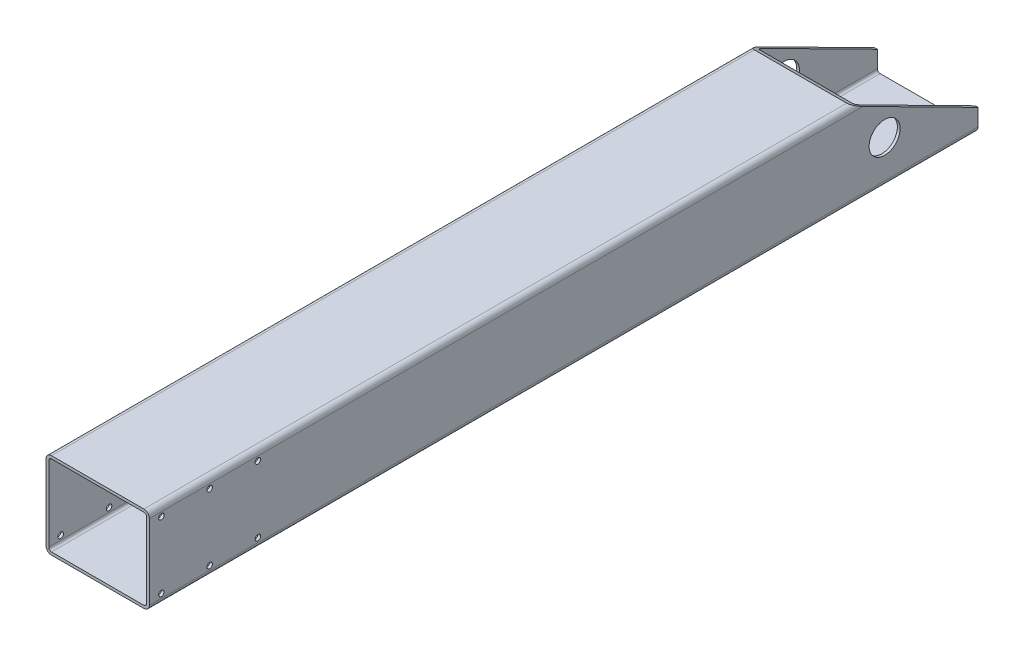
SolidWorks part; units mm, degrees
material "Q355"
ref_plane "前视基准面" through (0, 0, 0) normal (0, 0, 1) x (1, 0, 0)
ref_plane "上视基准面" through (0, 0, 0) normal (0, 1, 0) x (1, 0, 0)
ref_plane "右视基准面" through (0, 0, 0) normal (1, 0, 0) x (0, 0, -1)
sketch "草图1" plane through (0, 0, 0) normal (0, 0, 1) x (1, 0, 0)
  line L0 (-134, 117) -> (134, 117)
  line L5 (-134, 125) -> (134, 125)
  line L6 (-150, 109) -> (-150, -109)
  line L11 (-134, -125) -> (134, -125)
  line L12 (150, 109) -> (150, -109)
  line L13 (142, 109) -> (142, -109)
  line L14 (-134, -117) -> (134, -117)
  line L15 (-142, 109) -> (-142, -109)
  line L16 (134, 109) -> (-134, -109) construction
  arc A0 (-134, -125) -> (-150, -109) centre (-134, -109) cw
  arc A1 (134, -125) -> (150, -109) centre (134, -109) ccw
  arc A2 (150, 109) -> (134, 125) centre (134, 109) ccw
  arc A3 (-134, 125) -> (-150, 109) centre (-134, 109) ccw
  arc A4 (142, 109) -> (134, 117) centre (134, 109) ccw
  arc A5 (134, -117) -> (142, -109) centre (134, -109) ccw
  arc A6 (-134, -117) -> (-142, -109) centre (-134, -109) cw
  arc A7 (-134, 117) -> (-142, 109) centre (-134, 109) ccw
  point P10 (150, -125)
  point P14 (150, 125)
  point P17 (-150, 125)
  dimension "D3" = 16
  dimension "D1" = 300
  dimension "D2" = 250
  dimension "D4" = 8
extrude "凸台-拉伸1" add sketch "草图1" against normal blind 2405
sketch "草图2" plane through (150, 0, 0) normal (1, 0, 0) x (0, 0, -1)
  line L0 (0, 0) -> (315, 0) construction
  line L1 (0, -109) -> (0, 109) construction
  line L2 (2405, 125) -> (0, 125) construction
  line L3 (2405, -125) -> (0, -125) construction
  line L4 (2405, -109) -> (2405, 109) construction
  line L5 (2405, -60) -> (2040, 125)
  line L6 (2040, 125) -> (2405, 125)
  line L7 (2405, 125) -> (2405, -60)
  circle A0 centre (35, 96.5) radius 8
  circle A1 centre (175, 96.5) radius 8
  circle A2 centre (315, 96.5) radius 8
  circle A3 centre (2134, 0) radius 45
  circle A4 centre (1260, 50) radius 50 construction
  circle A5 centre (315, -96.5) radius 8
  circle A6 centre (175, -96.5) radius 8
  circle A7 centre (35, -96.5) radius 8
  dimension "D1" = 35
  dimension "D2" = 140
  dimension "D3" = 140
  dimension "D4" = 96.5
  dimension "D5" = 16
  dimension "D7" = 100
  dimension "D8" = 271
  dimension "D9" = 75
  dimension "D10" = 125
  dimension "D11" = 90
  dimension "D12" = 185
  dimension "D13" = 365
extrude "切除-拉伸1" cut sketch "草图2" against normal through all
sketch "草图3" plane through (0, -125, 0) normal (0, -1, 0) x (1, 0, 0)
  line L1 (-35, -1980.5) -> (35, -1980.5)
  line L2 (-35, -1980.5) -> (-35, -2070.5)
  line L3 (-35, -2070.5) -> (35, -2070.5)
  line L4 (35, -1980.5) -> (35, -2070.5)
  line L5 (-150, -2405) -> (-150, 0) construction
  line L6 (-134, -2405) -> (134, -2405) construction
  dimension "D1" = 90
  dimension "D2" = 70
  dimension "D3" = 334.5
  dimension "D4" = 115
extrude "切除-拉伸2" cut sketch "草图3" against normal up to next
